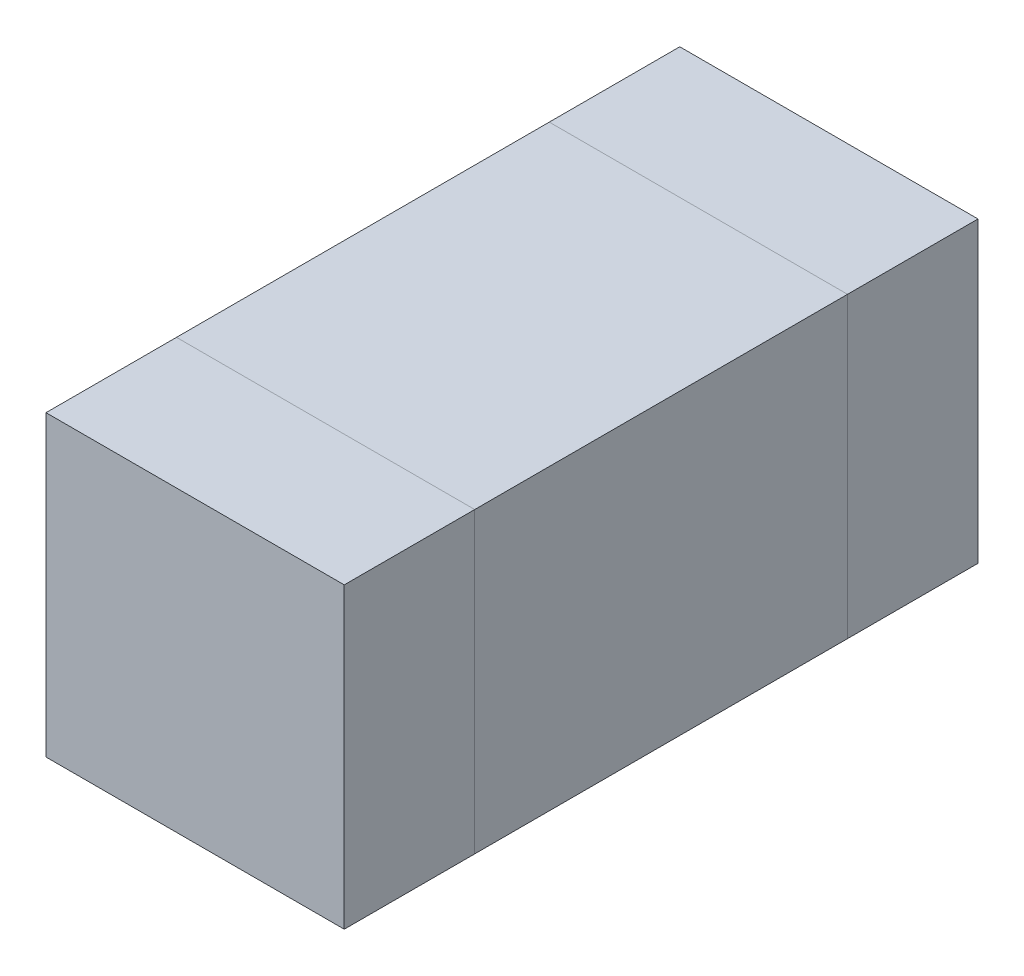
SolidWorks part; units mm, degrees
ref_plane "Front Plane" through (0, 0, 0) normal (0, 0, 1) x (1, 0, 0)
ref_plane "Top Plane" through (0, 0, 0) normal (0, 1, 0) x (1, 0, 0)
ref_plane "Right Plane" through (0, 0, 0) normal (1, 0, 0) x (0, 0, -1)
sketch "Sketch1" plane through (0, 0, 0) normal (0, 1, 0) x (1, 0, 0)
  line L1 (-0.4, 0.5) -> (0.4, 0.5)
  line L2 (-0.4, 0.5) -> (-0.4, -0.5)
  line L3 (-0.4, -0.5) -> (0.4, -0.5)
  line L4 (0.4, 0.5) -> (0.4, -0.5)
  line L5 (-0.4, 0.5) -> (0.4, -0.5) construction
  line L6 (-0.4, -0.5) -> (0.4, 0.5) construction
  point P0 (0, 0)
  dimension "D1" = 1
  dimension "D2" = 0.8
extrude "MB" add sketch "Sketch1" along normal blind 0.8
sketch "Sketch2" plane through (0, 0, 0.5) normal (0, 0, 1) x (1, 0, 0)
  line L4 (-0.4, 0) -> (0.4, 0)
  line L5 (0.4, 0) -> (0.4, 0.8)
  line L6 (0.4, 0.8) -> (-0.4, 0.8)
  line L7 (-0.4, 0.8) -> (-0.4, 0)
  line L8 (-0.4, 0) -> (0.4, 0)
  line L9 (0.4, 0) -> (0.4, 0.8)
  line L10 (0.4, 0.8) -> (-0.4, 0.8)
  line L11 (-0.4, 0.8) -> (-0.4, 0)
  dimension "D1" = 0
extrude "SB L" add sketch "Sketch2" along normal blind 0.35 separate body
sketch "Sketch3" plane through (0, 0, -0.5) normal (0, 0, -1) x (-1, 0, 0)
  line L4 (-0.4, 0) -> (0.4, 0)
  line L5 (0.4, 0) -> (0.4, 0.8)
  line L6 (0.4, 0.8) -> (-0.4, 0.8)
  line L7 (-0.4, 0.8) -> (-0.4, 0)
  line L8 (-0.4, 0) -> (0.4, 0)
  line L9 (0.4, 0) -> (0.4, 0.8)
  line L10 (0.4, 0.8) -> (-0.4, 0.8)
  line L11 (-0.4, 0.8) -> (-0.4, 0)
  dimension "D1" = 0
extrude "SB R" add sketch "Sketch3" along normal blind 0.35 separate body
